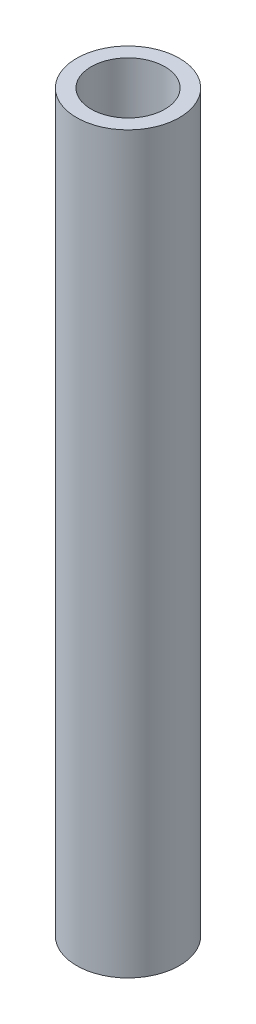
SolidWorks part; units mm, degrees
ref_plane "Front Plane" through (0, 0, 0) normal (0, 0, 1) x (1, 0, 0)
ref_plane "Top Plane" through (0, 0, 0) normal (0, 1, 0) x (1, 0, 0)
ref_plane "Right Plane" through (0, 0, 0) normal (1, 0, 0) x (0, 0, -1)
sketch "Sketch1" plane through (0, 0, 0) normal (0, 1, 0) x (1, 0, 0)
  circle A0 centre (0, 0) radius 7.6454
  circle A1 centre (0, 0) radius 10.668
  dimension "D1" = 21.336
  dimension "D2" = 15.2908
extrude "Boss-Extrude1" add sketch "Sketch1" along normal blind 152.4
ref_plane "Plane1" through (0, 76.2, 0) normal (0, 1, 0) x (1, 0, 0)
